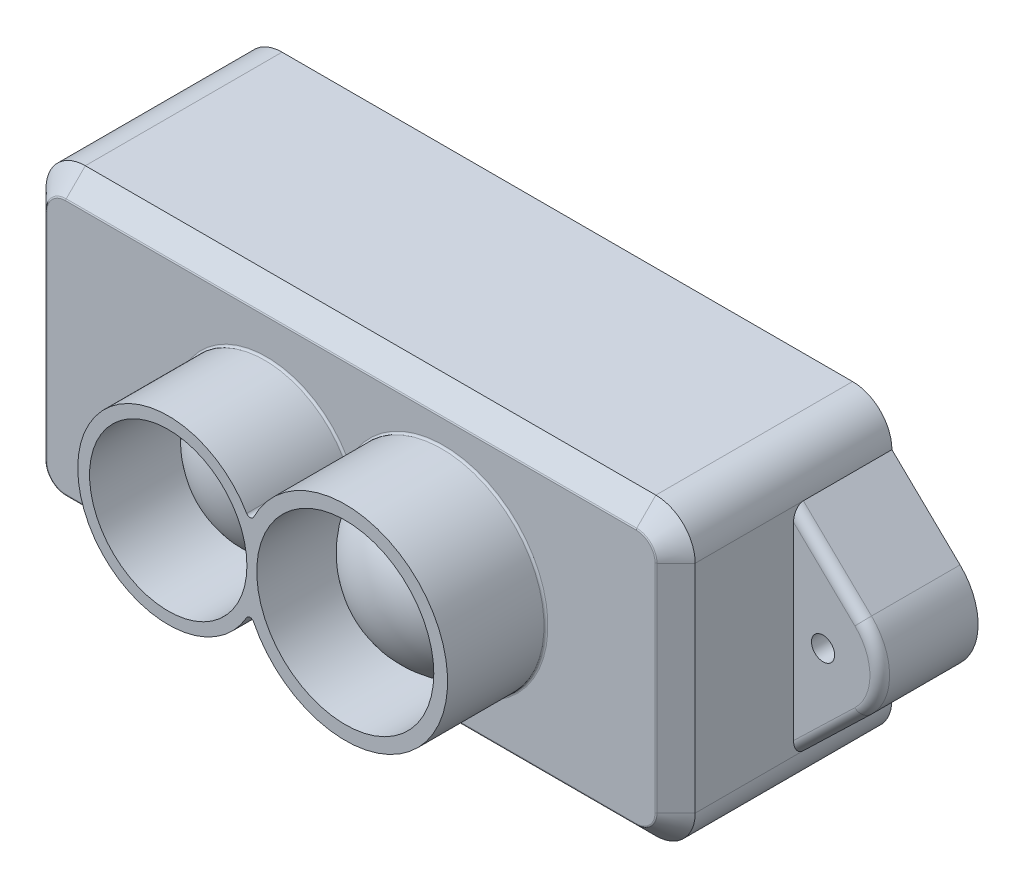
SolidWorks part; units mm, degrees
ref_plane "Plan de face" through (0, 0, 0) normal (0, 0, 1) x (1, 0, 0)
ref_plane "Plan de dessus" through (0, 0, 0) normal (0, 1, 0) x (1, 0, 0)
ref_plane "Plan de droite" through (0, 0, 0) normal (1, 0, 0) x (0, 0, -1)
sketch "Esquisse1" plane through (0, 0, 0) normal (0, 0, 1) x (1, 0, 0)
  line L1 (-14.5, 7.5) -> (14.5, 7.5)
  line L2 (-16.5, 5.5) -> (-16.5, -5.5)
  line L3 (-14.5, -7.5) -> (14.5, -7.5)
  line L4 (16.5, 5.5) -> (16.5, -5.5)
  arc A0 (-16.5, -5.5) -> (-14.5, -7.5) centre (-14.5, -5.5) ccw
  arc A1 (14.5, -7.5) -> (16.5, -5.5) centre (14.5, -5.5) ccw
  arc A2 (16.5, 5.5) -> (14.5, 7.5) centre (14.5, 5.5) ccw
  arc A3 (-14.5, 7.5) -> (-16.5, 5.5) centre (-14.5, 5.5) ccw
  point P4 (0, 7.5)
  point P5 (-16.5, 0)
  point P9 (-16.5, -7.5)
  point P12 (16.5, -7.5)
  point P15 (16.5, 7.5)
  point P18 (16.5, 0)
  dimension "D3" = 2
  dimension "D1" = 33
  dimension "D2" = 15
extrude "Boss.-Extru.1" add sketch "Esquisse1" along normal blind 11
sketch "Esquisse2" plane through (0, 0, 0) normal (0, 0, -1) x (-1, 0, 0)
  line L0 (16.5, 5.5) -> (19.9642, 2.1595)
  line L1 (16.5, 5.5) -> (16.5, -5.5) construction
  line L2 (19.9642, -2.1595) -> (16.5, -5.5)
  line L3 (16.5, -5.5) -> (16.5, 5.5)
  circle A0 centre (18, 0) radius 0.5875
  arc A1 (19.9642, -2.1595) -> (19.9642, 2.1595) centre (17.8818, 0) ccw
  point P4 (16.5, 0)
  point P12 (22.2037, 0)
  dimension "D1" = 1.5
  dimension "D2" = 3
  dimension "D3" = 1.175
extrude "Boss.-Extru.2" add sketch "Esquisse2" against normal blind 5
mirror "Symétrie1" about plane through (0, 0, 0) normal (1, 0, 0) of "Boss.-Extru.2"
sketch "Esquisse3" plane through (0, 0, 11) normal (0, 0, 1) x (1, 0, 0)
  circle A0 centre (4.7135, 0) radius 4.5
  circle A1 centre (-4.2865, 0) radius 4
  arc A2 (-0.2998, 2.2949) -> (-0.2998, -2.2949) centre (-4.2865, 0) ccw
  arc A3 (0.0528, 2.306) -> (0.0528, -2.306) centre (4.7135, 0) cw
  arc A4 (0.0528, -2.306) -> (-0.2998, -2.2949) centre (-0.1265, -2.3947) ccw
  arc A5 (0.0528, 2.306) -> (-0.2998, 2.2949) centre (-0.1265, 2.3947) cw
  dimension "D1" = 9
  dimension "D2" = 8
  dimension "D4" = 5.2
  dimension "D5" = 4.6
  dimension "D6" = 0.2
  dimension "D3" = 9
extrude "Boss.-Extru.3" add sketch "Esquisse3" along normal blind 5
sketch "Esquisse5" plane through (0, 0, 11) normal (0, 0, 1) x (1, 0, 0)
  circle A0 centre (4.7135, 0) radius 4.5 construction
  circle A1 centre (-4.2865, 0) radius 4 construction
  circle A2 centre (4.7135, 0) radius 4.5
  circle A3 centre (-4.2865, 0) radius 4
extrude "Boss.-Extru.4" [suppressed] add sketch "Esquisse5" along normal blind 4
chamfer "Chanfrein1" distance 1 angle 45 8 edges at (16.5, 0, 11) (15.9142, 6.9142, 11) (15.9142, -6.9142, 11) (0, 7.5, 11) (0, -7.5, 11) (-15.9142, 6.9142, 11) (-15.9142, -6.9142, 11) (-16.5, 0, 11)
fillet "Congé3" radius 0.5 6 edges at (18.2321, -3.8298, 5) (18.2321, 3.8298, 5) (-18.2321, -3.8298, 5) (-20.8818, 0, 5) (20.8818, 0, 5) (-18.2321, 3.8298, 5)
fillet "Congé4" radius 0.1 12 edges at (9.9135, 0, 11) (-8.8865, 0, 11) (0, -6.5, 11) (-15.2071, -6.2071, 11) (-15.5, 0, 11) (-15.2071, 6.2071, 11) (0, 6.5, 11) (15.2071, 6.2071, 11) (15.5, 0, 11) (15.2071, -6.2071, 11) (-0.1202, 2.1948, 11) (-0.1202, -2.1948, 11)
sketch "Esquisse6" plane through (0, 0, 0) normal (0, 0, -1) x (-1, 0, 0)
  line L6 (-15.4329, 5.1398) -> (-15.4329, -5.1398)
  line L8 (15.4329, 5.1398) -> (15.4329, -5.1398)
  line L12 (15.4329, -5.1398) -> (19.27, -1.4397)
  line L13 (19.27, 1.4397) -> (15.4329, 5.1398)
  line L14 (14.5, 6.5) -> (-14.5, 6.5)
  line L15 (-15.4329, 5.1398) -> (-19.27, 1.4397)
  line L16 (-19.27, -1.4397) -> (-15.4329, -5.1398)
  line L17 (-14.5, -6.5) -> (14.5, -6.5)
  line L20 (14.5, 6.5) -> (-14.5, 6.5)
  line L23 (-14.5, -6.5) -> (14.5, -6.5)
  arc A12 (14.5, -6.5) -> (15.4329, -5.1398) centre (14.5, -5.5) ccw
  arc A13 (19.27, -1.4397) -> (19.27, 1.4397) centre (17.8818, 0) ccw
  arc A14 (15.4329, 5.1398) -> (14.5, 6.5) centre (14.5, 5.5) ccw
  arc A15 (-14.5, 6.5) -> (-15.4329, 5.1398) centre (-14.5, 5.5) ccw
  arc A16 (-19.27, 1.4397) -> (-19.27, -1.4397) centre (-17.8818, 0) ccw
  arc A17 (-15.4329, -5.1398) -> (-14.5, -6.5) centre (-14.5, -5.5) ccw
  arc A18 (14.5, -6.5) -> (15.4329, -5.1398) centre (14.5, -5.5) ccw
  arc A20 (15.4329, 5.1398) -> (14.5, 6.5) centre (14.5, 5.5) ccw
  arc A21 (-14.5, 6.5) -> (-15.4329, 5.1398) centre (-14.5, 5.5) ccw
  arc A23 (-15.4329, -5.1398) -> (-14.5, -6.5) centre (-14.5, -5.5) ccw
  dimension "D1" = 1
extrude "Enlèv. mat.-Extru.1" cut sketch "Esquisse6" against normal blind 6
ref_axis "Axe1" through (-4.2865, 0, 16) along (0, 0, -1)
ref_axis "Axe2" through (4.7135, 0, 16) along (0, 0, -1)
sketch "Esquisse8" plane through (0, 0, 0) normal (0, 1, 0) x (1, 0, 0)
  line L0 (4.7135, -11.1) -> (0.2135, -11.1)
  line L1 (0.0528, -11.1) -> (9.9135, -11.1) construction
  line L3 (0.2135, -11) -> (0.2135, -16) construction
  line L5 (4.7135, -16) -> (4.7135, -11) construction
  line L6 (4.7135, -11.1) -> (4.7135, -14.5285)
  arc A1 (0.2135, -11.1) -> (4.7135, -14.5285) centre (4.7135, -9.8611) ccw
  point P4 (4.7135, -14.13)
  point P5 (4.3578, -9.4167)
  point P10 (4.4543, -9.6211)
  point P12 (0, 0)
  point P14 (4.7135, -10.2548)
  point P15 (4.7135, -12.3889)
  point P16 (4.7135, -14.5285)
revolve "Révolution2" add sketch "Esquisse8" angle 360 about axis through (4.7135, 0, 16) along (0, 0, -1)
sketch "Esquisse9" plane through (0, 0, 0) normal (0, 1, 0) x (1, 0, 0)
  line L0 (-4.2865, -16) -> (-4.2865, -11) construction
  line L1 (-8.2865, -11) -> (-8.2865, -16) construction
  line L2 (-0.2998, -11.1) -> (-8.8865, -11.1) construction
  line L3 (-8.2865, -11.1) -> (-4.2865, -11.1)
  line L4 (-4.2865, -11.1) -> (-4.2865, -13.5015)
  arc A0 (-8.2865, -11.1) -> (-4.2865, -13.5015) centre (-4.2865, -8.9696) ccw
revolve "Révolution3" add sketch "Esquisse9" angle 360 about axis through (-4.2865, 0, 16) along (0, 0, -1)
